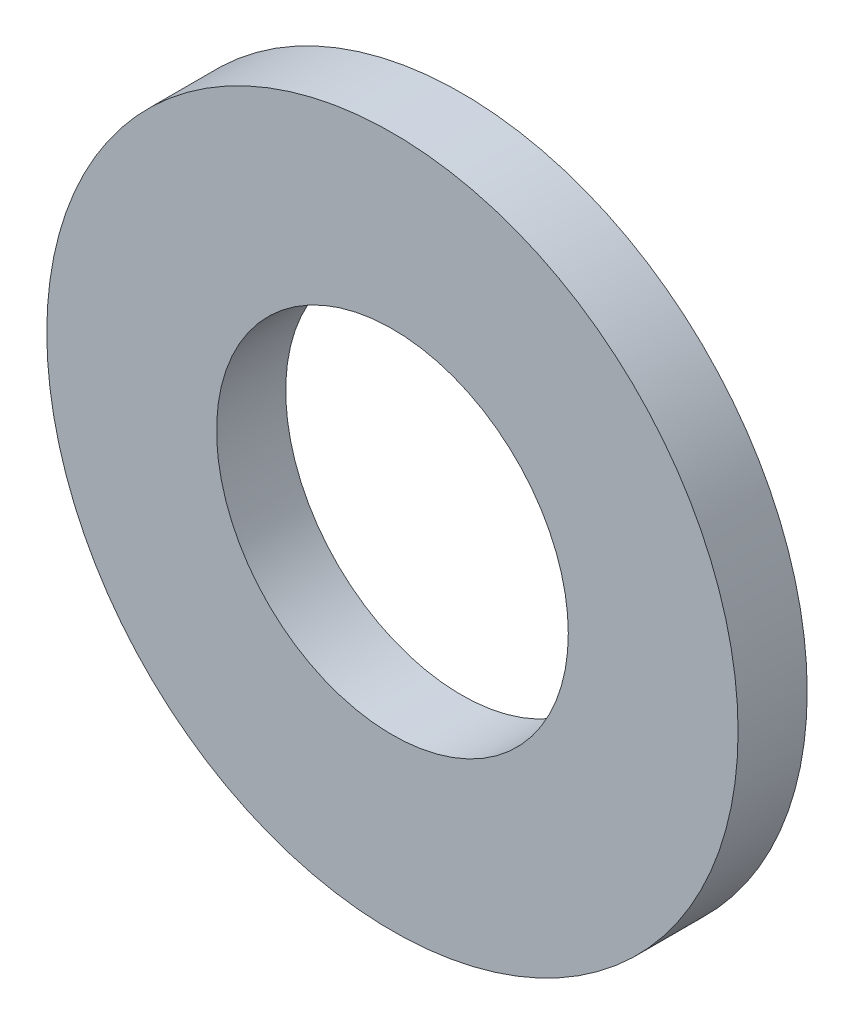
SolidWorks part; units mm, degrees
ref_plane "Front Plane" through (0, 0, 0) normal (0, 0, 1) x (1, 0, 0)
ref_plane "Top Plane" through (0, 0, 0) normal (0, 1, 0) x (1, 0, 0)
ref_plane "Right Plane" through (0, 0, 0) normal (1, 0, 0) x (0, 0, -1)
sketch "Sketch1" plane through (0, 0, 0) normal (0, 0, 1) x (1, 0, 0)
  circle A0 centre (0, 0) radius 4.0386
  circle A1 centre (0, 0) radius 7.9375
extrude "Boss-Extrude1" add sketch "Sketch1" along normal blind 1.5875
